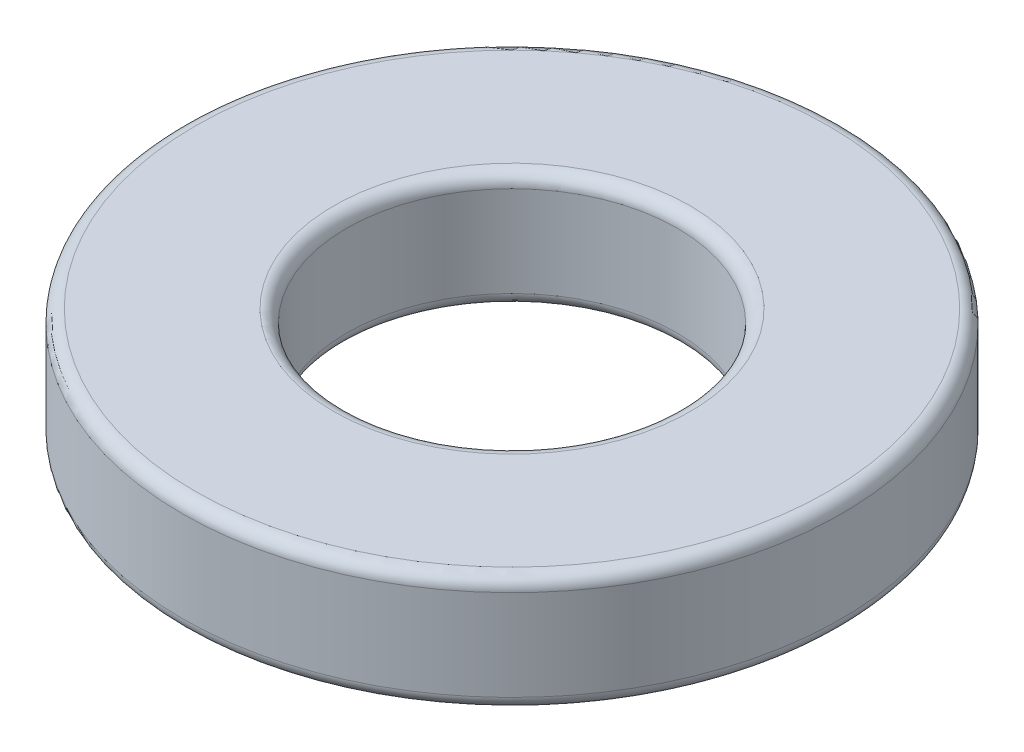
SolidWorks part; units mm, degrees
ref_plane "Front Plane" through (0, 0, 0) normal (0, 0, 1) x (1, 0, 0)
ref_plane "Top Plane" through (0, 0, 0) normal (0, 1, 0) x (1, 0, 0)
ref_plane "Right Plane" through (0, 0, 0) normal (1, 0, 0) x (0, 0, -1)
sketch "Sketch1" plane through (0, 0, 0) normal (0, 1, 0) x (1, 0, 0)
  circle A0 centre (0, 0) radius 25.425
  circle A1 centre (0, 0) radius 12.75
  dimension "D1" = 50.85
  dimension "D2" = 25.5
extrude "Boss-Extrude1" add sketch "Sketch1" along normal blind 9
fillet "Fillet1" radius 1 4 edges at (0, 0, 25.425) (0, 9, 25.425) (0, 0, 12.75) (0, 9, 12.75)
